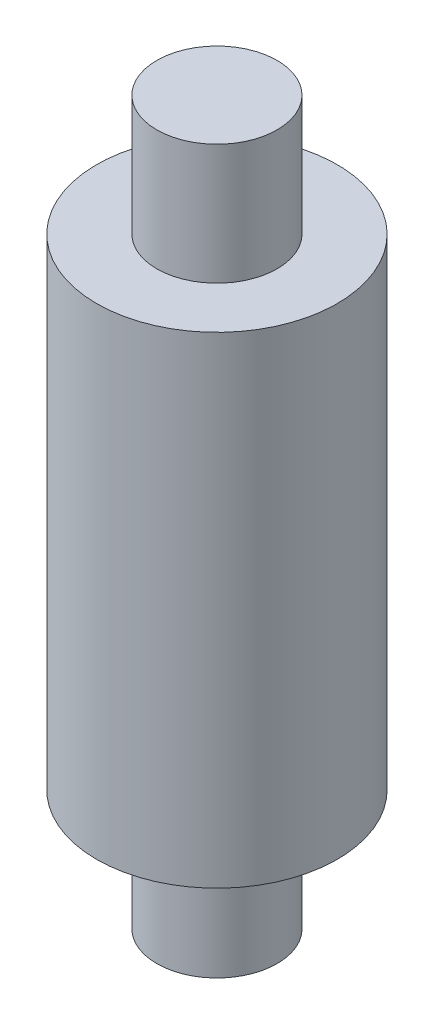
SolidWorks part; units mm, degrees
ref_plane "前视基准面" through (0, 0, 0) normal (0, 0, 1) x (1, 0, 0)
ref_plane "上视基准面" through (0, 0, 0) normal (0, 1, 0) x (1, 0, 0)
ref_plane "右视基准面" through (0, 0, 0) normal (1, 0, 0) x (0, 0, -1)
other "Configuration Table"
sketch "草图1" plane through (0, 0, 0) normal (0, 1, 0) x (1, 0, 0)
  circle A0 centre (0, 0) radius 1
  dimension "D1" = 2
extrude "凸台-拉伸1" add sketch "草图1" along normal blind 2
sketch "草图2" plane through (0, 2, 0) normal (0, 1, 0) x (1, 0, 0)
  circle A0 centre (0, 0) radius 2
  dimension "D1" = 4
extrude "凸台-拉伸2" add sketch "草图2" along normal blind 8
sketch "草图3" plane through (0, 10, 0) normal (0, 1, 0) x (1, 0, 0)
  circle A0 centre (0, 0) radius 1
  dimension "D1" = 2
extrude "凸台-拉伸3" add sketch "草图3" along normal blind 2
